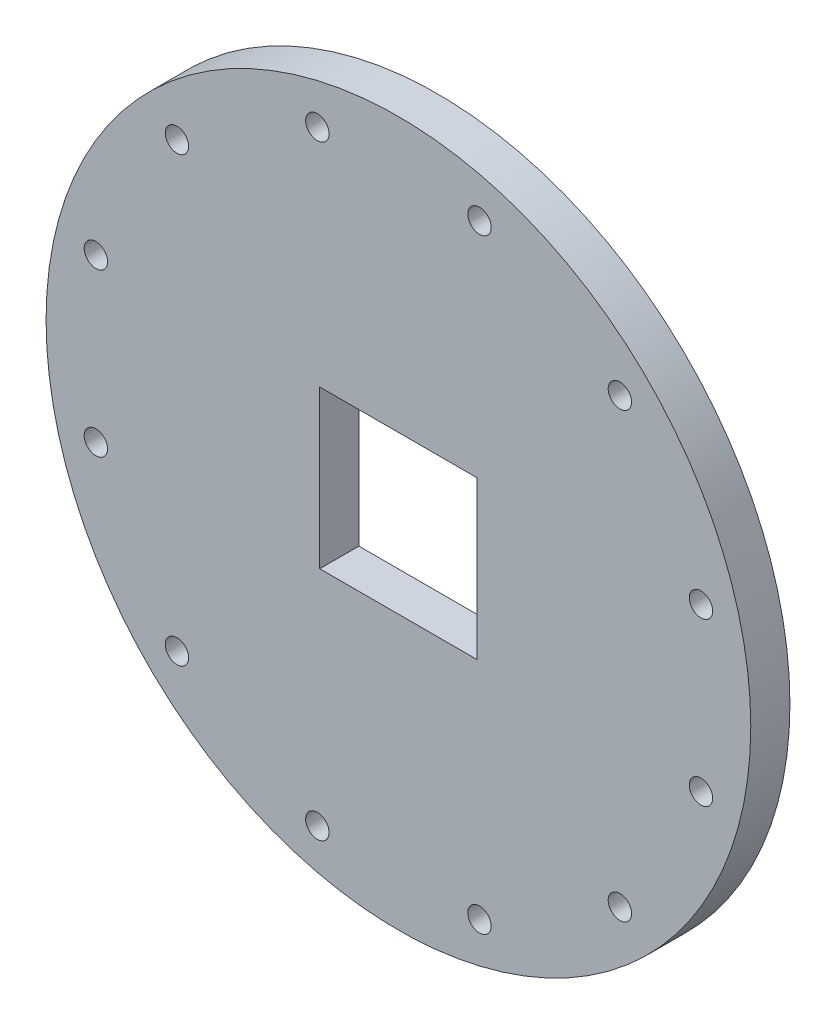
SolidWorks part; units mm, degrees
material "PET"
ref_plane "Front Plane" through (0, 0, 0) normal (0, 0, 1) x (1, 0, 0)
ref_plane "Top Plane" through (0, 0, 0) normal (0, 1, 0) x (1, 0, 0)
ref_plane "Right Plane" through (0, 0, 0) normal (1, 0, 0) x (0, 0, -1)
sketch "Sketch1" plane through (0, 0, 0) normal (0, 0, 1) x (1, 0, 0)
  line L1 (-12.7635, -12.7635) -> (12.7635, -12.7635)
  line L2 (-12.7635, -12.7635) -> (-12.7635, 12.7635)
  line L3 (-12.7635, 12.7635) -> (12.7635, 12.7635)
  line L4 (12.7635, -12.7635) -> (12.7635, 12.7635)
  line L5 (-12.7635, -12.7635) -> (12.7635, 12.7635) construction
  line L6 (-12.7635, 12.7635) -> (12.7635, -12.7635) construction
  circle A0 centre (0, 0) radius 57.15
  dimension "D1" = 114.3
  dimension "D2" = 25.527
  dimension "D3" = 25.527
extrude "Boss-Extrude1" add sketch "Sketch1" along normal blind 6.35
hole_wizard "#6 Clearance Hole1" positions "Sketch2" profile "Sketch3" hole size "#6" standard "ANSI Inch" end condition through all
sketch "Sketch2" plane through (0, 0, 0) normal (0, 0, -1) x (-1, 0, 0)
  line L0 (0, 0) -> (35.921, 35.921) construction
  line L3 (0, 0) -> (57.15, 0) construction
  circle A0 centre (0, 0) radius 57.15 construction
  point P0 (35.921, 35.921)
  dimension "D1" = 50.8
  dimension "D2" = 45
sketch "Sketch3" plane through (-35.921, 35.921, 0) normal (1, 0, 0) x (0, 1, 0)
  line L0 (0, 0) -> (0, 6.35)
  line L1 (0, 6.35) -> (1.8986, 6.35)
  line L2 (1.8986, 6.35) -> (1.8986, 0)
  line L5 (1.8986, 0) -> (0, 0)
  line L11 (0, -6.35) -> (0, 107.95) construction
  dimension "Thru Hole Dia." = 3.7973
  dimension "Thru Hole Depth" = 6.35
pattern_circular "CirPattern1" count 12 over 360 about axis through (0, 0, 0) along (0, 0, 1) of "#6 Clearance Hole1"
sketch "Sketch4" plane through (0, 0, 0) normal (0, 0, -1) x (-1, 0, 0)
  circle A0 centre (35.921, 35.921) radius 3.4925
  dimension "D1" = 6.985
extrude "Cut-Extrude1" cut sketch "Sketch4" against normal blind 3.048
pattern_circular "CirPattern2" count 12 over 360 about axis through (0, 0, 0) along (0, 0, 1) of "Cut-Extrude1"
